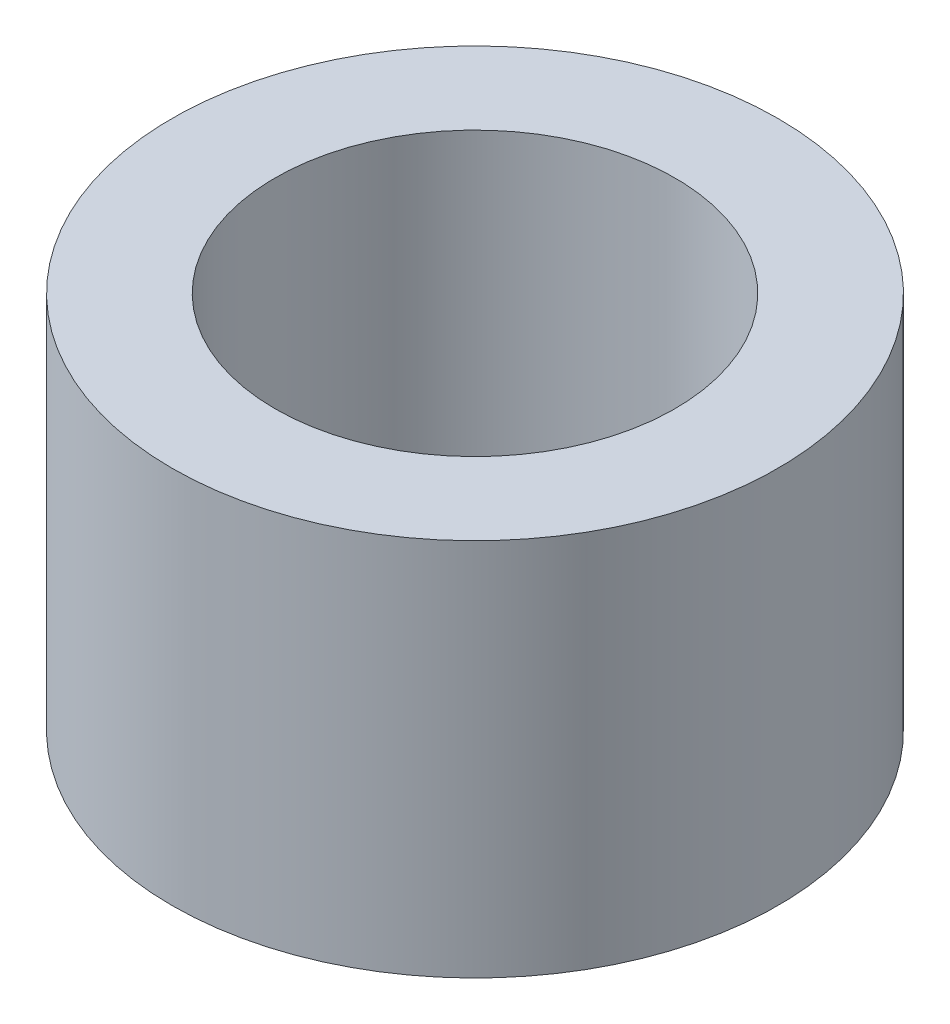
SolidWorks part; units mm, degrees
ref_plane "Front Plane" through (0, 0, 0) normal (0, 0, 1) x (1, 0, 0)
ref_plane "Top Plane" through (0, 0, 0) normal (0, 1, 0) x (1, 0, 0)
ref_plane "Right Plane" through (0, 0, 0) normal (1, 0, 0) x (0, 0, -1)
sketch "Sketch1" plane through (0, 0, 0) normal (0, 1, 0) x (1, 0, 0)
  circle A0 centre (0, 0) radius 8.382
  circle A1 centre (0, 0) radius 12.7
  dimension "D2" = 25.4
  dimension "D1" = 16.764
extrude "Boss-Extrude1" add sketch "Sketch1" along normal blind 15.875
sketch "Sketch2" plane through (0, 0, 0) normal (0, -1, 0) x (1, 0, 0)
  line L0 (-12.7, 0) -> (12.7, 0)
  line L1 (12.7, 0) -> (12.7, 12.7)
  line L2 (12.7, 12.7) -> (-12.7, 12.7)
  line L3 (-12.7, 12.7) -> (-12.7, 0)
  circle A0 centre (0, 0) radius 12.7 construction
